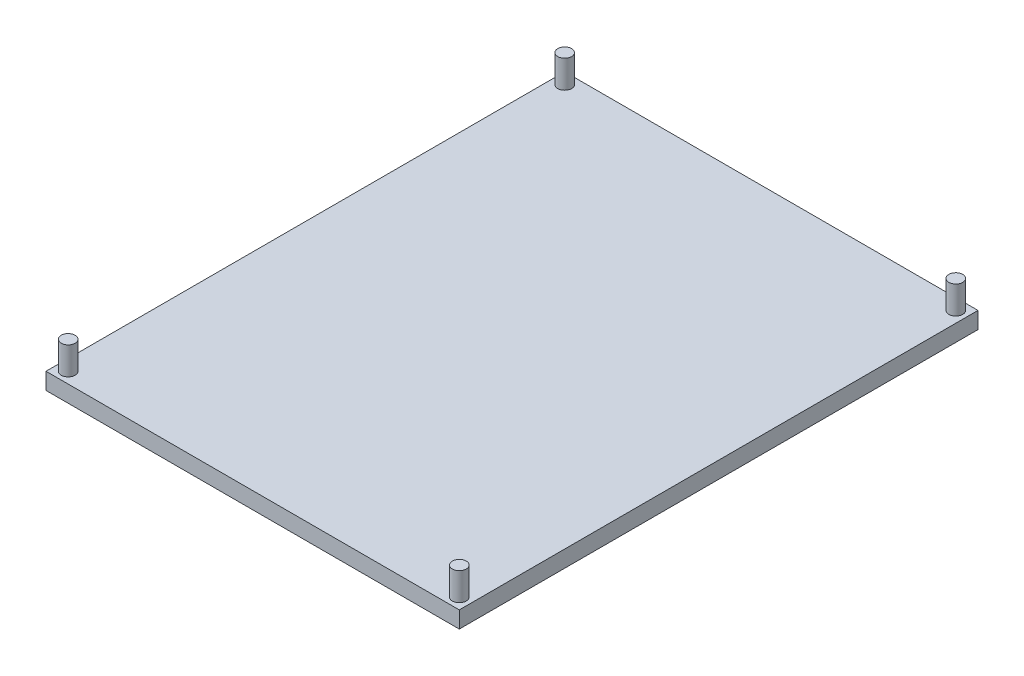
SolidWorks part; units mm, degrees
ref_plane "Front Plane" through (0, 0, 0) normal (0, 0, 1) x (1, 0, 0)
ref_plane "Top Plane" through (0, 0, 0) normal (0, 1, 0) x (1, 0, 0)
ref_plane "Right Plane" through (0, 0, 0) normal (1, 0, 0) x (0, 0, -1)
sketch "Sketch1" plane through (0, 0, 0) normal (0, 1, 0) x (1, 0, 0)
  line L1 (-37.25, 46.75) -> (37.25, 46.75)
  line L2 (-37.25, 46.75) -> (-37.25, -46.75)
  line L3 (-37.25, -46.75) -> (37.25, -46.75)
  line L4 (37.25, 46.75) -> (37.25, -46.75)
  line L5 (-37.25, 46.75) -> (37.25, -46.75) construction
  line L6 (-37.25, -46.75) -> (37.25, 46.75) construction
  point P0 (0, 0)
  dimension "D1" = 74.5
  dimension "D2" = 93.5
extrude "Boss-Extrude1" add sketch "Sketch1" along normal blind 3
sketch "Sketch2" plane through (0, 3, 0) normal (0, 1, 0) x (1, 0, 0)
  line L0 (37.25, 46.75) -> (-37.25, 46.75) construction
  line L1 (-37.25, 46.75) -> (-37.25, -46.75) construction
  line L2 (37.25, -46.75) -> (37.25, 46.75) construction
  line L3 (-37.25, -46.75) -> (37.25, -46.75) construction
  circle A0 centre (-35.25, 44.75) radius 1.25
  circle A1 centre (35.25, 44.75) radius 1.25
  circle A2 centre (-35.25, -44.75) radius 1.25
  circle A3 centre (35.25, -44.75) radius 1.25
  point P16 (0, 0)
  dimension "D1" = 2.5
  dimension "D4" = 2.5
  dimension "D7" = 2.5
  dimension "D10" = 2.5
  dimension "D2" = 2
  dimension "D3" = 2
  dimension "D5" = 2
  dimension "D6" = 2
  dimension "D8" = 2
  dimension "D9" = 2
  dimension "D11" = 2
  dimension "D12" = 2
extrude "Boss-Extrude2" add sketch "Sketch2" along normal blind 5
